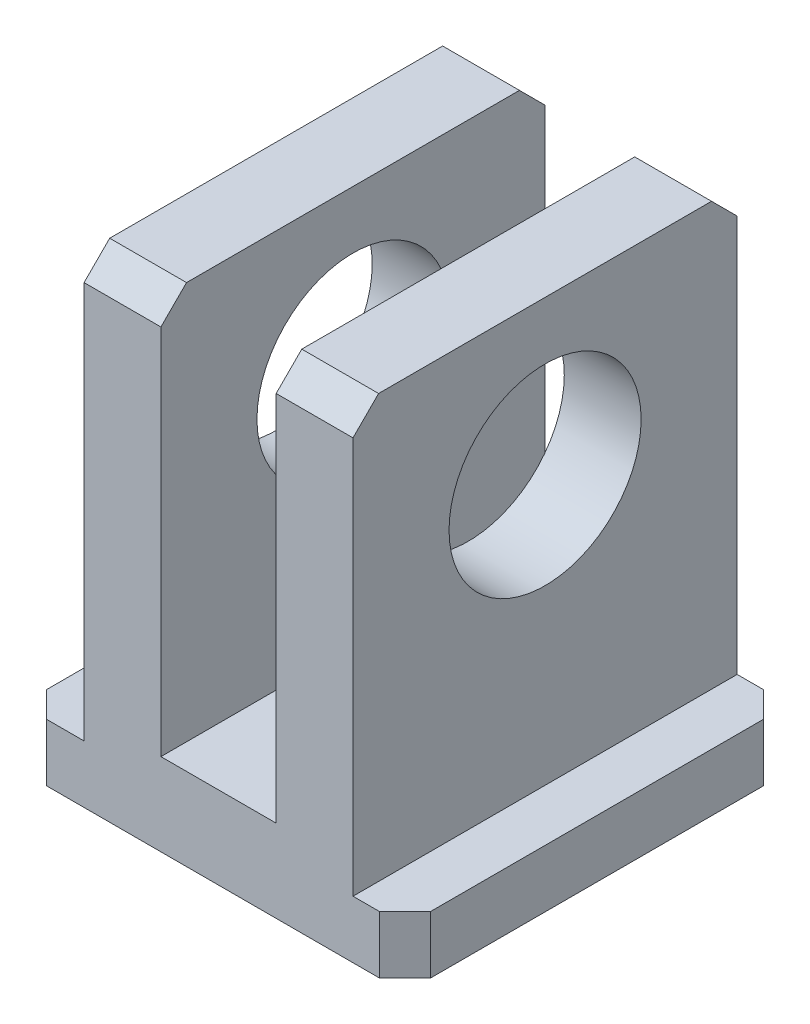
SolidWorks part; units mm, degrees
ref_plane "前视基准面" through (0, 0, 0) normal (0, 0, 1) x (1, 0, 0)
ref_plane "上视基准面" through (0, 0, 0) normal (0, 1, 0) x (1, 0, 0)
ref_plane "右视基准面" through (0, 0, 0) normal (1, 0, 0) x (0, 0, -1)
other "Configuration Table"
sketch "草图1" plane through (0, 0, 0) normal (1, 0, 0) x (0, 0, -1)
  line L0 (0, 0) -> (30, 0)
  line L1 (30, 0) -> (30, 37.5)
  line L2 (30, 37.5) -> (0, 37.5)
  line L3 (0, 37.5) -> (0, 0)
  dimension "D1" = 30
  dimension "D2" = 37.5
extrude "凸台-拉伸2" add sketch "草图1" along normal mid plane 30
sketch "草图3" plane through (0, 0, 0) normal (0, 0, 1) x (1, 0, 0)
  line L0 (0.4389, 0) -> (0.4389, 37.5) construction
  line L2 (-15, 4.5) -> (-10.0611, 4.5)
  line L3 (-15, 37.5) -> (-15, 0) construction
  line L4 (-10.0611, 4.5) -> (-10.0611, 37.5)
  line L5 (-10.0611, 37.5) -> (-4.0611, 37.5)
  line L6 (15, 37.5) -> (-15, 37.5) construction
  line L7 (-4.0611, 37.5) -> (-4.0611, 6.4412)
  line L8 (-4.0611, 6.4412) -> (4.9389, 6.4412)
  line L9 (4.9389, 37.5) -> (4.9389, 6.4412)
  line L10 (10.9389, 37.5) -> (4.9389, 37.5)
  line L11 (15.8778, 4.5) -> (10.9389, 4.5)
  line L12 (10.9389, 4.5) -> (10.9389, 37.5)
  line L13 (-4.0611, 37.5) -> (4.9389, 37.5)
  point P16 (0.4389, 6.4412)
  line M10 (-15, 37.5) -> (-15, 0)
  line M12 (15, 0) -> (15, 37.5)
  line M13 (15, 37.5) -> (-15, 37.5)
  dimension "D1" = 33
  dimension "D2" = 21
  dimension "D3" = 9
extrude "切除-拉伸1" cut sketch "草图3" against normal through all contours L8 L0 L13 L7 | L0 L8 L9 M13 | L2 L4 M13 M10 | L12 L11 M12 M13
sketch "草图4" plane through (-10.0611, 0, 0) normal (-1, 0, 0) x (0, 0, 1)
  line L0 (-15, -1.5789) -> (-15, 35.9211) construction
  line L3 (0, 0) -> (-30, 0) construction
  circle A0 centre (-15, 25.5) radius 7.5
  dimension "D2" = 15
  dimension "D1" = 25.5
extrude "切除-拉伸2" cut sketch "草图4" against normal through all contours A0
chamfer "倒角1" distance 2 angle 45 8 edges at (-15, 2.25, 0) (15, 2.25, 0) (15, 2.25, -30) (-15, 2.25, -30) (7.9389, 37.5, 0) (-7.0611, 37.5, 0) (-7.0611, 37.5, -30) (7.9389, 37.5, -30)
